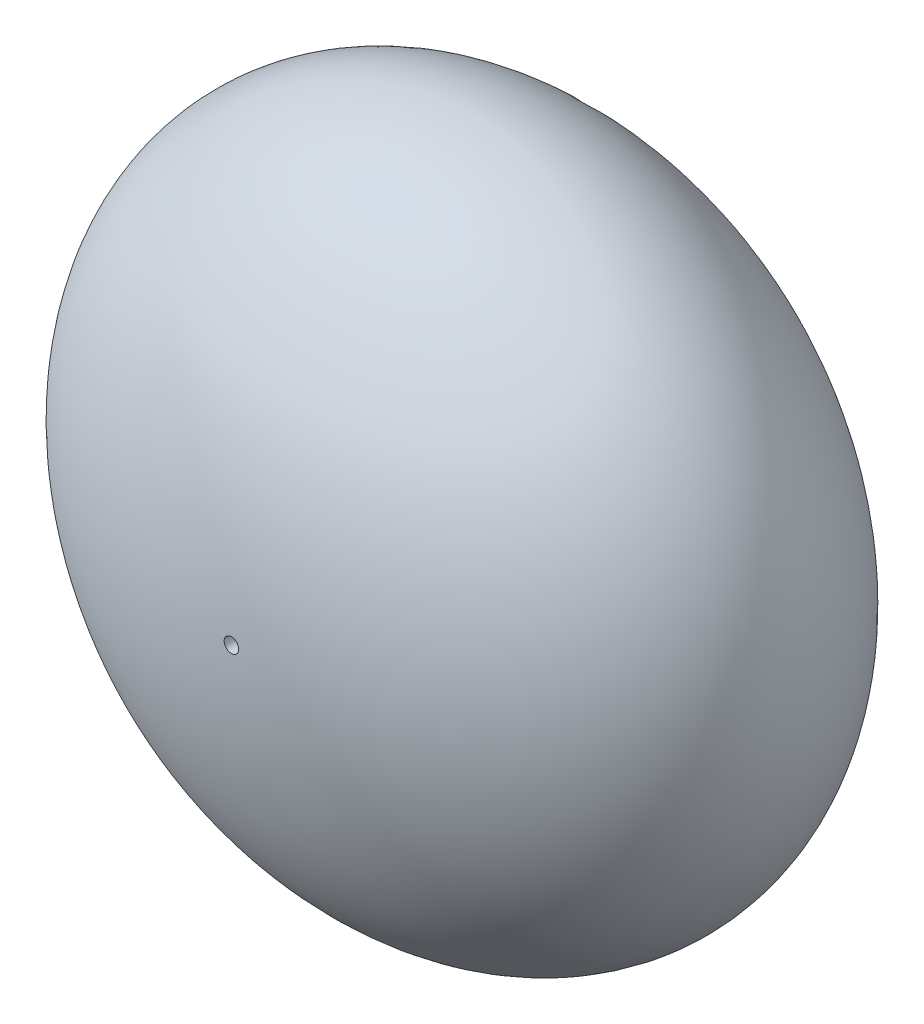
SolidWorks part; units mm, degrees
ref_plane "Front Plane" through (0, 0, 0) normal (0, 0, 1) x (1, 0, 0)
ref_plane "Top Plane" through (0, 0, 0) normal (0, 1, 0) x (1, 0, 0)
ref_plane "Right Plane" through (0, 0, 0) normal (1, 0, 0) x (0, 0, -1)
other "Center of Mass"
sketch "Sketch1" plane through (0, 0, 0) normal (0, 1, 0) x (1, 0, 0)
  line L0 (0, 17.5) -> (0, -17.5) construction
  line L1 (0, 17.5) -> (0, -17.5)
  ellipse E0 centre (0, 0) end of major axis (-26.25, 0) minor radius 17.5 (0, -17.5) -> (0, 17.5) ccw
  dimension "D1" = 17.5
  dimension "D2" = 26.25
revolve "Revolve4" add sketch "Sketch1" angle 360 about L0
sketch "Sketch3" plane through (0, 0, 0) normal (0, 0, 1) x (1, 0, 0)
  circle A0 centre (0, 0) radius 7
  dimension "D1" = 14
extrude "Cut-Extrude1" cut sketch "Sketch3" along normal blind 13
sketch "Sketch4" plane through (0, 0, 0) normal (0, 0, 1) x (1, 0, 0)
  circle A0 centre (0, 0) radius 0.55
  dimension "D1" = 1.1
extrude "Cut-Extrude2" cut sketch "Sketch4" against normal through all both and the other way through all
sketch "Sketch5" plane through (0, 0, 0) normal (0, 1, 0) x (1, 0, 0)
  circle A0 centre (0, 10) radius 1.3
  dimension "D1" = 2.6
  dimension "D2" = 10
extrude "Cut-Extrude3" cut sketch "Sketch5" against normal through all both and the other way through all
